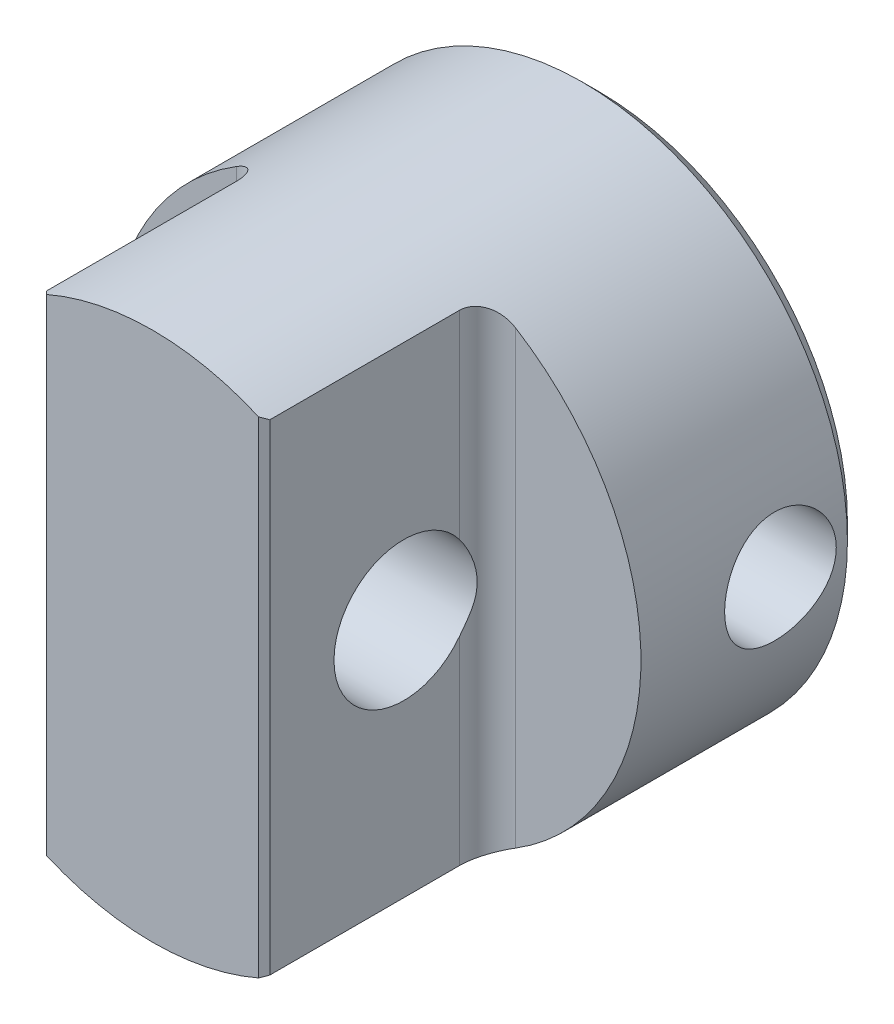
SolidWorks part; units mm, degrees
ref_plane "Спереди" through (0, 0, 0) normal (0, 0, 1) x (1, 0, 0)
ref_plane "Сверху" through (0, 0, 0) normal (0, 1, 0) x (1, 0, 0)
ref_plane "Справа" through (0, 0, 0) normal (1, 0, 0) x (0, 0, -1)
sketch "Эскиз1" plane through (0, 0, 0) normal (0, 0, 1) x (1, 0, 0)
  circle A0 centre (0, 0) radius 47.5
extrude "Бобышка-Вытянуть1" add sketch "Эскиз1" along normal blind 80
sketch "Эскиз2" plane through (0, 0, 80) normal (0, 0, 1) x (1, 0, 0)
  line L0 (0, 47.5) -> (0, -65.2008) construction
  line L1 (20, -43.0842) -> (20, 43.0842)
  line L2 (-20, -43.0842) -> (-20, 43.0842)
  arc A0 (-20, 43.0842) -> (-20, -43.0842) centre (0, 0) ccw
  circle A1 centre (0, 0) radius 47.5 construction
  arc A2 (20, -43.0842) -> (20, 43.0842) centre (0, 0) ccw
extrude "Вырез-Вытянуть1" cut sketch "Эскиз2" against normal blind 40
fillet "Скругление1" radius 5 2 edges at (-20, 0, 40) (20, 0, 40)
sketch "Эскиз3" plane through (-20, 0, 0) normal (-1, 0, 0) x (0, 0, 1)
  line L0 (45, 0) -> (80, 0) construction
  line L1 (45, 43.0842) -> (45, -43.0842) construction
  line L2 (80, -43.0842) -> (80, 43.0842) construction
  circle A0 centre (55, 0) radius 12.5
extrude "Вырез-Вытянуть2" cut sketch "Эскиз3" against normal through all
chamfer "Фаска1" distance 1 angle 45 2 edges at (-20, 0, 80) (20, 0, 80)
chamfer "Фаска2" distance 3 angle 45 1 edges at (47.5, 0, 0)
sketch "Эскиз4" plane through (0, 0, 0) normal (1, 0, 0) x (0, 0, -1)
  line L0 (-82.3564, 0) -> (29.3425, 0) construction
  circle A0 centre (-15, 0) radius 10
extrude "Вырез-Вытянуть3" cut sketch "Эскиз4" against normal through all and the other way through all
